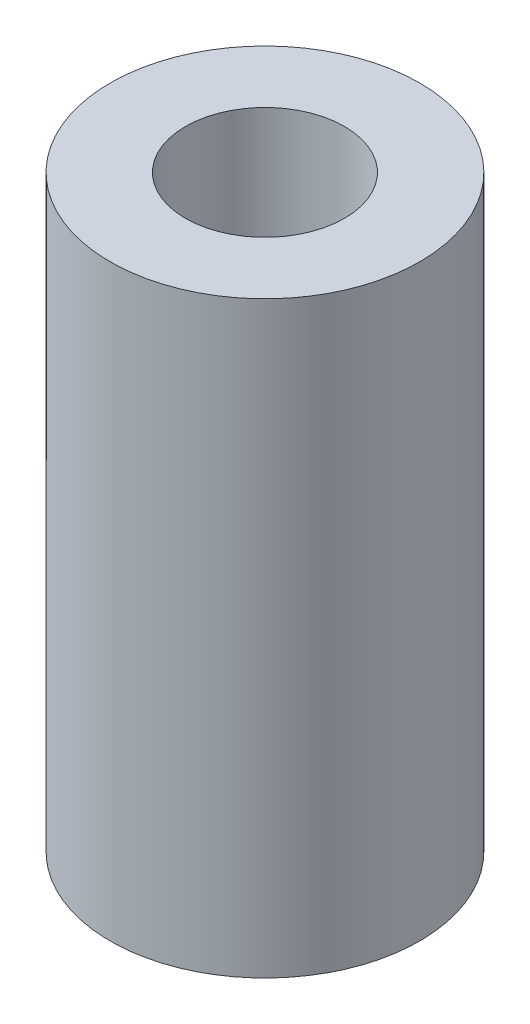
SolidWorks part; units mm, degrees
material "PLA"
ref_plane "Front Plane" through (0, 0, 0) normal (0, 0, 1) x (1, 0, 0)
ref_plane "Top Plane" through (0, 0, 0) normal (0, 1, 0) x (1, 0, 0)
ref_plane "Right Plane" through (0, 0, 0) normal (1, 0, 0) x (0, 0, -1)
sketch "Sketch1" plane through (0, 0, 0) normal (0, 1, 0) x (1, 0, 0)
  circle A0 centre (0, 0) radius 6.35
  circle A1 centre (0, 0) radius 3.2639
  dimension "D1" = 12.7
  dimension "D2" = 6.5278
extrude "Boss-Extrude1" add sketch "Sketch1" along normal blind 24.13
